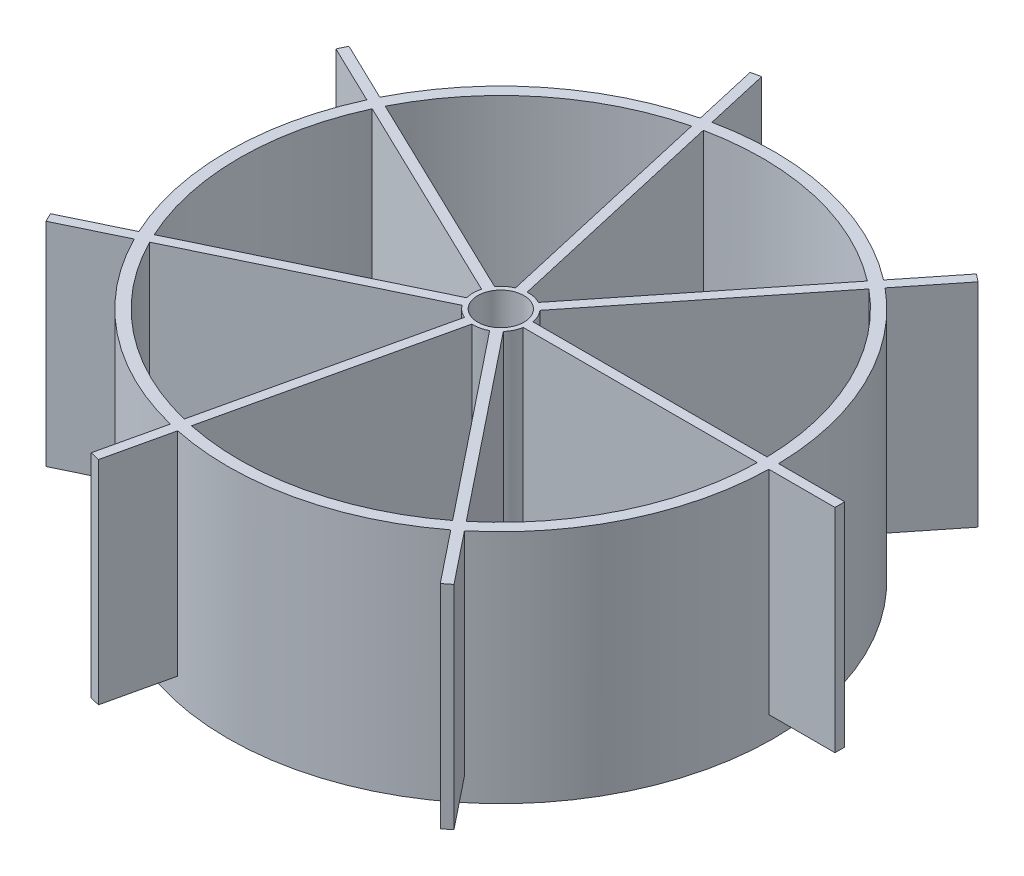
SolidWorks part; units mm, degrees
ref_plane "Front Plane" through (0, 0, 0) normal (0, 0, 1) x (1, 0, 0)
ref_plane "Top Plane" through (0, 0, 0) normal (0, 1, 0) x (1, 0, 0)
ref_plane "Right Plane" through (0, 0, 0) normal (1, 0, 0) x (0, 0, -1)
sketch "Sketch1" plane through (0, 0, 0) normal (0, 1, 0) x (1, 0, 0)
  line L0 (0, 0) -> (113.1987, 0) construction
  line L1 (-55, 0) -> (55, 0) construction
  line L2 (0, 0) -> (56.5994, -98.033) construction
  line L3 (0, 0) -> (-56.5994, -98.033) construction
  line L4 (0, 0) -> (-113.1987, 0) construction
  line L5 (0, 0) -> (-56.5994, 98.033) construction
  line L6 (0, 0) -> (56.5994, 98.033) construction
  circle A0 centre (0, 0) radius 113.1987
  point P14 (0, 0)
  dimension "D1" = 6
extrude "Boss-Extrude1" add sketch "Sketch1" along normal blind 10
sketch "Sketch3" plane through (0, 10, 0) normal (0, 1, 0) x (1, 0, 0)
  line L0 (11.8131, 2.1096) -> (146.803, 2.1096)
  line L1 (0, 0) -> (40.9485, 0) construction
  line L2 (11.8131, -2.1096) -> (146.803, -2.1096)
  line L3 (9.0147, -7.9205) -> (93.1796, -113.4599)
  line L4 (5.716, -10.5512) -> (89.8808, -116.0905)
  line L5 (-0.5719, -11.9864) -> (-30.61, -143.5918)
  line L6 (-4.6854, -11.0475) -> (-34.7235, -142.6529)
  line L7 (-9.7279, -7.0262) -> (-131.3496, -65.5962)
  line L8 (-11.5586, -3.2248) -> (-133.1803, -61.7947)
  line L9 (-11.5586, 3.2248) -> (-133.1803, 61.7947)
  line L10 (-9.7279, 7.0262) -> (-131.3496, 65.5962)
  line L11 (-4.6854, 11.0475) -> (-34.7235, 142.6529)
  line L12 (-0.5719, 11.9864) -> (-30.61, 143.5918)
  line L13 (5.716, 10.5512) -> (89.8808, 116.0905)
  line L14 (9.0147, 7.9205) -> (93.1796, 113.4599)
  circle A1 centre (0, 0) radius 10
  arc A2 (11.8131, 2.1096) -> (9.0147, 7.9205) centre (0, 0) ccw
  arc A3 (146.803, -2.1096) -> (146.803, 2.1096) centre (0, 0) ccw
  circle A4 centre (0, 0) radius 12 construction
  arc A5 (89.8808, -116.0905) -> (93.1796, -113.4599) centre (0, 0) ccw
  arc A6 (-34.7235, -142.6529) -> (-30.61, -143.5918) centre (0, 0) ccw
  arc A7 (-133.1803, -61.7947) -> (-131.3496, -65.5962) centre (0, 0) ccw
  arc A8 (-131.3496, 65.5962) -> (-133.1803, 61.7947) centre (0, 0) ccw
  arc A9 (-30.61, 143.5918) -> (-34.7235, 142.6529) centre (0, 0) ccw
  arc A10 (93.1796, 113.4599) -> (89.8808, 116.0905) centre (0, 0) ccw
  arc A11 (9.0147, -7.9205) -> (11.8131, -2.1096) centre (0, 0) ccw
  arc A12 (-0.5719, -11.9864) -> (5.716, -10.5512) centre (0, 0) ccw
  arc A13 (-9.7279, -7.0262) -> (-4.6854, -11.0475) centre (0, 0) ccw
  arc A14 (-11.5586, 3.2248) -> (-11.5586, -3.2248) centre (0, 0) ccw
  arc A15 (-4.6854, 11.0475) -> (-9.7279, 7.0262) centre (0, 0) ccw
  arc A16 (5.716, 10.5512) -> (-0.5719, 11.9864) centre (0, 0) ccw
  point P38 (0, 0)
  dimension "D1" = 2
extrude "Boss-Extrude2" add sketch "Sketch3" along normal blind 92
sketch "Sketch4" plane through (0, 10, 0) normal (0, 1, 0) x (1, 0, 0)
  circle A0 centre (0, 0) radius 113.1987
  circle A1 centre (0, 0) radius 118.1987
  dimension "D1" = 5
extrude "Boss-Extrude3" add sketch "Sketch4" against normal up to surface and the other way up to surface
sketch "Sketch5" plane through (0, 10, 0) normal (0, 1, 0) x (1, 0, 0)
  line L0 (-113.1734, 2.3936) -> (-11.538, 2.3936) construction
  line L1 (-7.8419, 8.7955) -> (-58.6596, 96.8143) construction
  line L2 (-54.5138, 99.2078) -> (-3.6961, 11.189) construction
  line L3 (3.6961, 11.189) -> (54.5138, 99.2078) construction
  line L4 (-58.6596, -96.8143) -> (-7.8419, -8.7955) construction
  line L5 (-11.538, -2.3936) -> (-113.1734, -2.3936) construction
  line L6 (54.5138, -99.2078) -> (3.6961, -11.189) construction
  line L7 (-3.6961, -11.189) -> (-54.5138, -99.2078) construction
  line L8 (113.1734, -2.3936) -> (11.538, -2.3936) construction
  line L9 (7.8419, -8.7955) -> (58.6596, -96.8143) construction
  line L10 (58.6596, 96.8143) -> (7.8419, 8.7955) construction
  line L11 (11.538, 2.3936) -> (113.1734, 2.3936) construction
  line L12 (-113.1734, 2.3936) -> (-11.538, 2.3936)
  line L13 (-7.8419, 8.7955) -> (-58.6596, 96.8143)
  line L14 (-54.5138, 99.2078) -> (-3.6961, 11.189)
  line L15 (3.6961, 11.189) -> (54.5138, 99.2078)
  line L16 (-58.6596, -96.8143) -> (-7.8419, -8.7955)
  line L17 (-11.538, -2.3936) -> (-113.1734, -2.3936)
  line L18 (54.5138, -99.2078) -> (3.6961, -11.189)
  line L19 (-3.6961, -11.189) -> (-54.5138, -99.2078)
  line L20 (113.1734, -2.3936) -> (11.538, -2.3936)
  line L21 (7.8419, -8.7955) -> (58.6596, -96.8143)
  line L22 (58.6596, 96.8143) -> (7.8419, 8.7955)
  line L23 (11.538, 2.3936) -> (113.1734, 2.3936)
  arc A0 (-7.8419, 8.7955) -> (-11.538, 2.3936) centre (0, 0) ccw construction
  arc A1 (-58.6596, 96.8143) -> (-113.1734, 2.3936) centre (0, 0) ccw construction
  arc A2 (3.6961, 11.189) -> (-3.6961, 11.189) centre (0, 0) ccw construction
  arc A3 (54.5138, 99.2078) -> (-54.5138, 99.2078) centre (0, 0) ccw construction
  arc A4 (-11.538, -2.3936) -> (-7.8419, -8.7955) centre (0, 0) ccw construction
  arc A5 (-113.1734, -2.3936) -> (-58.6596, -96.8143) centre (0, 0) ccw construction
  arc A6 (-3.6961, -11.189) -> (3.6961, -11.189) centre (0, 0) ccw construction
  arc A7 (-54.5138, -99.2078) -> (54.5138, -99.2078) centre (0, 0) ccw construction
  arc A8 (7.8419, -8.7955) -> (11.538, -2.3936) centre (0, 0) ccw construction
  arc A9 (58.6596, -96.8143) -> (113.1734, -2.3936) centre (0, 0) ccw construction
  arc A10 (11.538, 2.3936) -> (7.8419, 8.7955) centre (0, 0) ccw construction
  arc A11 (113.1734, 2.3936) -> (58.6596, 96.8143) centre (0, 0) ccw construction
  arc A12 (-7.8419, 8.7955) -> (-11.538, 2.3936) centre (0, 0) ccw
  arc A13 (-58.6596, 96.8143) -> (-113.1734, 2.3936) centre (0, 0) ccw
  arc A14 (3.6961, 11.189) -> (-3.6961, 11.189) centre (0, 0) ccw
  arc A15 (54.5138, 99.2078) -> (-54.5138, 99.2078) centre (0, 0) ccw
  arc A16 (-11.538, -2.3936) -> (-7.8419, -8.7955) centre (0, 0) ccw
  arc A17 (-113.1734, -2.3936) -> (-58.6596, -96.8143) centre (0, 0) ccw
  arc A18 (-3.6961, -11.189) -> (3.6961, -11.189) centre (0, 0) ccw
  arc A19 (-54.5138, -99.2078) -> (54.5138, -99.2078) centre (0, 0) ccw
  arc A20 (7.8419, -8.7955) -> (11.538, -2.3936) centre (0, 0) ccw
  arc A21 (58.6596, -96.8143) -> (113.1734, -2.3936) centre (0, 0) ccw
  arc A22 (11.538, 2.3936) -> (7.8419, 8.7955) centre (0, 0) ccw
  arc A23 (113.1734, 2.3936) -> (58.6596, 96.8143) centre (0, 0) ccw
extrude "Cut-Extrude1" cut sketch "Sketch5" against normal blind 59
